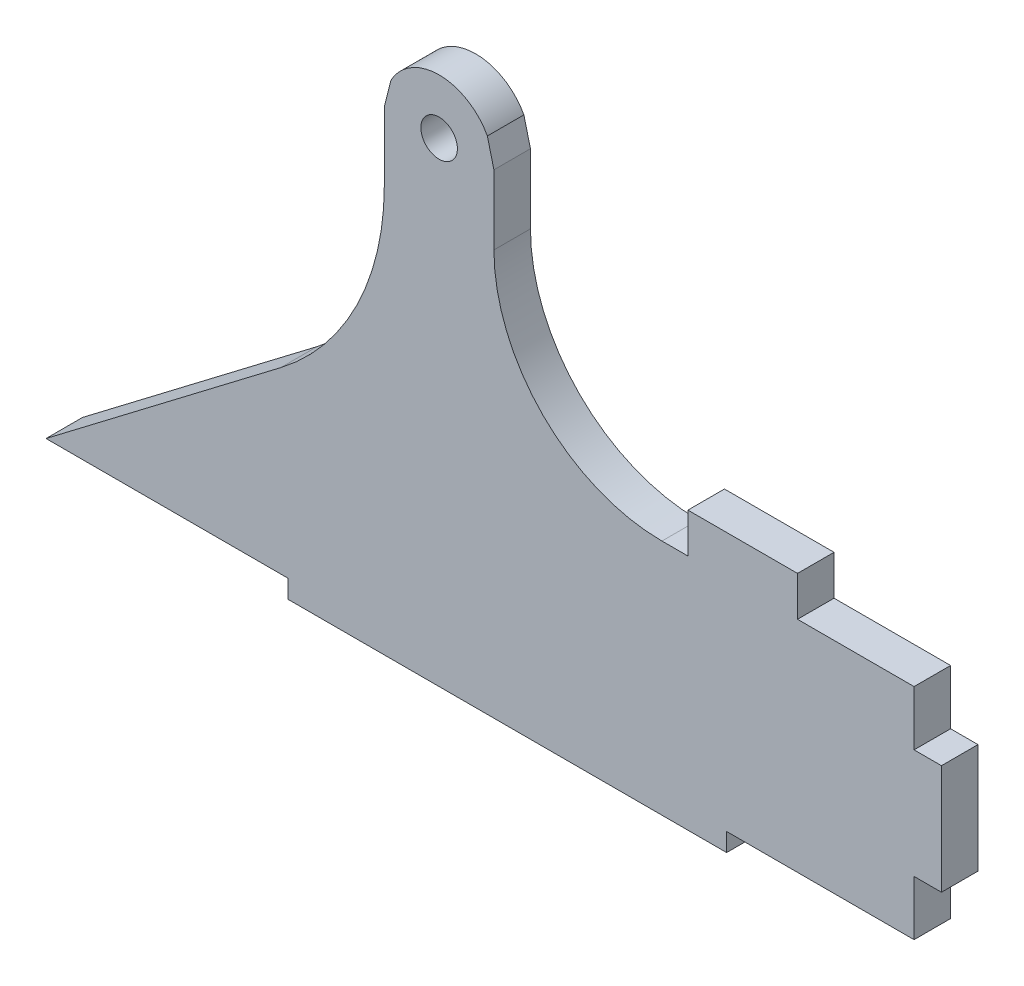
SolidWorks part; units mm, degrees
ref_plane "Front Plane" through (0, 0, 0) normal (0, 0, 1) x (1, 0, 0)
ref_plane "Top Plane" through (0, 0, 0) normal (0, 1, 0) x (1, 0, 0)
ref_plane "Right Plane" through (0, 0, 0) normal (1, 0, 0) x (0, 0, -1)
sketch "Sketch1" plane through (0, 0, 0) normal (0, 0, 1) x (1, 0, 0)
  line L0 (129.8035, 32.7787) -> (104.4035, 32.7787)
  line L1 (-171.9485, -43.4213) -> (-87.7475, -43.4213)
  line L4 (129.8035, -43.4213) -> (129.8035, -24.3713)
  line L5 (-171.9485, -43.4213) -> (129.8035, 32.7787) construction
  line L6 (-90.3867, 18.6912) -> (-171.9485, -43.4213)
  line L7 (-87.7475, -43.4213) -> (-87.7475, -49.7713)
  line L8 (-87.7475, -49.7713) -> (64.6525, -49.7713)
  line L9 (64.6525, -49.7713) -> (64.6525, -43.4213)
  line L16 (64.6525, -43.4213) -> (129.8035, -43.4213)
  line L17 (129.8035, 13.7287) -> (139.3285, 13.7287)
  line L18 (129.8035, 13.7287) -> (129.8035, 32.7787)
  line L19 (139.3285, -24.3713) -> (129.8035, -24.3713)
  line L20 (139.3285, 13.7287) -> (139.3285, -24.3713) construction
  line L21 (139.3285, 13.7287) -> (139.3285, -24.3713)
  line L23 (-16.2465, 115.3287) -> (-18.5281, 124.3689)
  line L24 (-61.2293, -49.7713) -> (-16.6946, -49.7713)
  line L27 (-52.0648, 124.3689) -> (-54.3465, 115.3287)
  line L29 (104.4035, 32.7787) -> (44.0785, 32.7787)
  line L30 (-16.2465, 91.1987) -> (-16.2465, 115.3287)
  line L31 (44.0785, 32.7787) -> (42.1735, 32.7787)
  line L32 (-54.3465, 115.3287) -> (-54.3465, 91.4383)
  line L33 (-54.3465, 91.4383) -> (-54.3465, 115.3287)
  line L34 (-16.2465, 115.3287) -> (-16.2465, 91.1987)
  line L36 (89.2905, 32.7787) -> (51.1905, 32.7787)
  line L37 (89.2905, 32.7787) -> (89.2905, 46.5975)
  line L38 (89.2905, 46.5975) -> (51.1905, 46.5975)
  line L39 (51.1905, 32.7787) -> (51.1905, 46.5975)
  circle A1 centre (-35.2965, 115.3287) radius 6.35
  arc A3 (-16.2465, 115.3287) -> (-54.3465, 115.3287) centre (-35.2965, 115.3287) ccw
  arc A5 (42.1735, 32.7787) -> (-16.2465, 91.1987) centre (42.1735, 91.1987) cw
  arc A6 (-54.3465, 91.4383) -> (-90.3867, 18.6912) centre (-145.7865, 91.4383) cw
  point P0 (0, 0)
  dimension "D17" = 38.1
  dimension "D13" = 165.1
  dimension "D14" = 12.7
  dimension "D15" = 165.1
  dimension "D16" = 58.42
  dimension "D7" = 91.44
  dimension "D2" = 301.752
  dimension "D3" = 76.2
  dimension "D4" = 6.35
  dimension "D5" = 152.4
  dimension "D6" = 38.1
  dimension "D8" = 50.038
  dimension "2.565" = 65.151
  dimension "D9" = 9.525
  dimension "D10" = 165.1
  dimension "D11" = 19.05
  dimension "D12" = 38.1
  dimension "D18" = 0
extrude "Boss-Extrude1" add sketch "Sketch1" along normal blind 12.7
